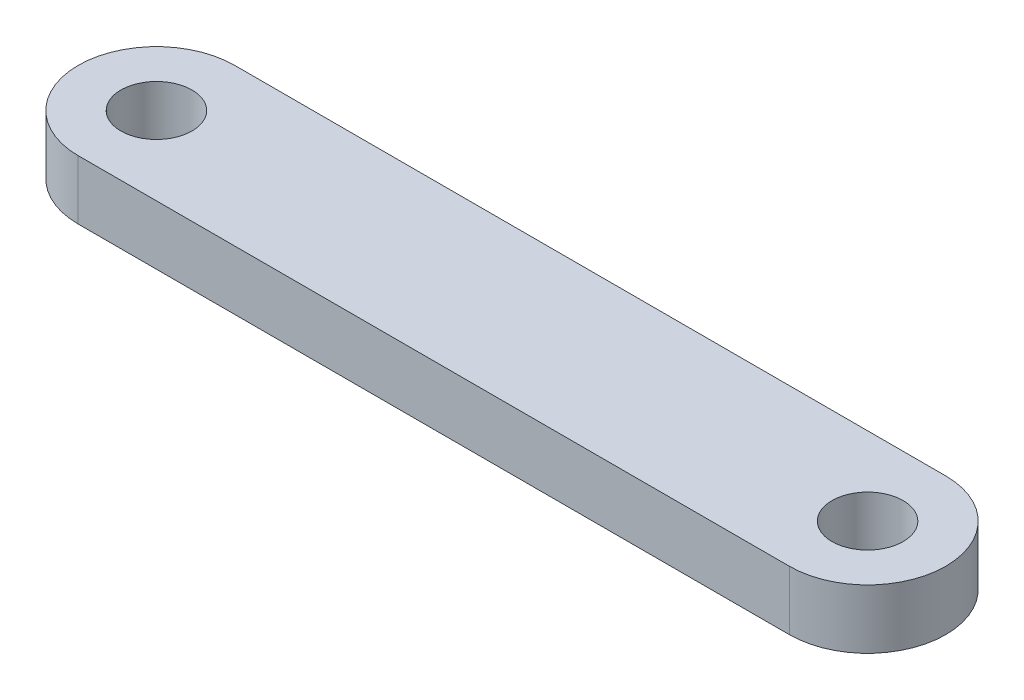
SolidWorks part; units mm, degrees
ref_plane "Front Plane" through (0, 0, 0) normal (0, 0, 1) x (1, 0, 0)
ref_plane "Top Plane" through (0, 0, 0) normal (0, 1, 0) x (1, 0, 0)
ref_plane "Right Plane" through (0, 0, 0) normal (1, 0, 0) x (0, 0, -1)
sketch "Sketch2" plane through (0, 0, 0) normal (0, 1, 0) x (1, 0, 0)
  line L0 (0, 0) -> (152.4, 0)
  line L1 (0, 0) -> (152.4, 0) construction
  line L2 (0, 16.764) -> (152.4, 16.764)
  line L3 (0, -16.764) -> (152.4, -16.764)
  arc A0 (0, 16.764) -> (0, -16.764) centre (0, 0) ccw
  arc A1 (152.4, -16.764) -> (152.4, 16.764) centre (152.4, 0) ccw
  circle A2 centre (0, 0) radius 7.62
  circle A3 centre (152.4, 0) radius 7.62
  point P3 (76.2, 0)
  dimension "D2" = 16.764
  dimension "D1" = 152.4
extrude "Boss-Extrude1" add sketch "Sketch2" along normal blind 12.7
